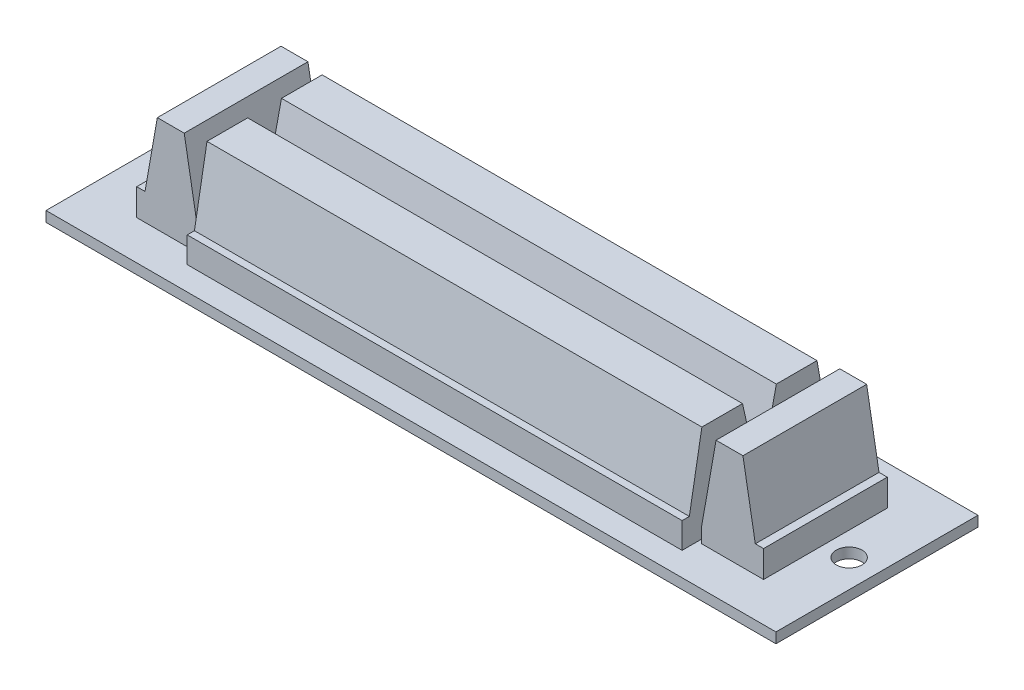
SolidWorks part; units mm, degrees
ref_plane "Front Plane" through (0, 0, 0) normal (0, 0, 1) x (1, 0, 0)
ref_plane "Top Plane" through (0, 0, 0) normal (0, 1, 0) x (1, 0, 0)
ref_plane "Right Plane" through (0, 0, 0) normal (1, 0, 0) x (0, 0, -1)
sketch "Sketch1" plane through (0, 0, 0) normal (0, 1, 0) x (1, 0, 0)
  line L0 (0, 12.446) -> (0, -12.446) construction
  line L1 (-44.958, 12.446) -> (44.958, 12.446)
  line L2 (-44.958, 12.446) -> (-44.958, -12.446)
  line L3 (-44.958, -12.446) -> (44.958, -12.446)
  line L4 (44.958, 12.446) -> (44.958, -12.446)
  line L5 (-44.958, 12.446) -> (44.958, -12.446) construction
  line L6 (-44.958, -12.446) -> (44.958, 12.446) construction
  circle A0 centre (-41.529, 0) radius 1.5875
  circle A1 centre (41.529, 0) radius 1.5875
  point P0 (0, 0)
  dimension "D3" = 3.175
  dimension "D1" = 89.916
  dimension "D2" = 24.892
  dimension "D4" = 83.058
extrude "Boss-Extrude1" add sketch "Sketch1" along normal mid plane 1.27
sketch "Sketch2" plane through (0, 0, 0) normal (1, 0, 0) x (0, 0, -1)
  line L0 (-9.525, 0.635) -> (-9.525, 3.81)
  line L1 (-9.525, 3.81) -> (-8.636, 3.81)
  line L2 (-8.636, 3.81) -> (-7.0908, 12.573)
  line L3 (-7.0908, 12.573) -> (-2.0835, 12.573)
  line L4 (-2.0835, 12.573) -> (0, 3.175)
  line L5 (0, 3.175) -> (0, 0.635) construction
  line L6 (-12.446, 0.635) -> (12.446, 0.635) construction
  line L7 (9.525, 0.635) -> (-9.525, 0.635)
  line L8 (9.525, 0.635) -> (9.525, 3.81)
  line L9 (9.525, 3.81) -> (8.636, 3.81)
  line L10 (8.636, 3.81) -> (7.0908, 12.573)
  line L11 (7.0908, 12.573) -> (2.0835, 12.573)
  line L12 (2.0835, 12.573) -> (0, 3.175)
  point P10 (-9.0805, 3.81)
  point P14 (9.0805, 3.81)
  dimension "D1" = 3.175
  dimension "D2" = 0.889
  dimension "D3" = 11.938
  dimension "D4" = 100
  dimension "D5" = 2.54
  dimension "D6" = 25
  dimension "D7" = 19.05
extrude "Boss-Extrude2" add sketch "Sketch2" along normal mid plane 60.96
sketch "Sketch3" plane through (0, 0, 0) normal (0, 0, 1) x (1, 0, 0)
  line L0 (-30.988, 0.635) -> (-30.988, 2.54)
  line L1 (-44.958, 0.635) -> (44.958, 0.635) construction
  line L2 (-30.988, 2.54) -> (-32.7571, 12.573)
  line L3 (-32.7571, 12.573) -> (-36.0692, 12.573)
  line L4 (-36.0692, 12.573) -> (-37.592, 3.937)
  line L5 (-37.592, 3.937) -> (-38.608, 3.937)
  line L6 (-38.608, 3.937) -> (-38.608, 0.635)
  line L7 (-38.608, 0.635) -> (-30.988, 0.635)
  line L8 (-30.48, 3.81) -> (-30.48, 0.635) construction
  dimension "D1" = 10
  dimension "D2" = 0.508
  dimension "D3" = 100
  dimension "D4" = 1.016
  dimension "D5" = 3.302
  dimension "D6" = 7.62
  dimension "D7" = 11.938
  dimension "D8" = 1.905
extrude "Boss-Extrude3" add sketch "Sketch3" along normal mid plane 15.24
mirror "Mirror1" about plane through (0, 0, 0) normal (1, 0, 0) of "Boss-Extrude3"
